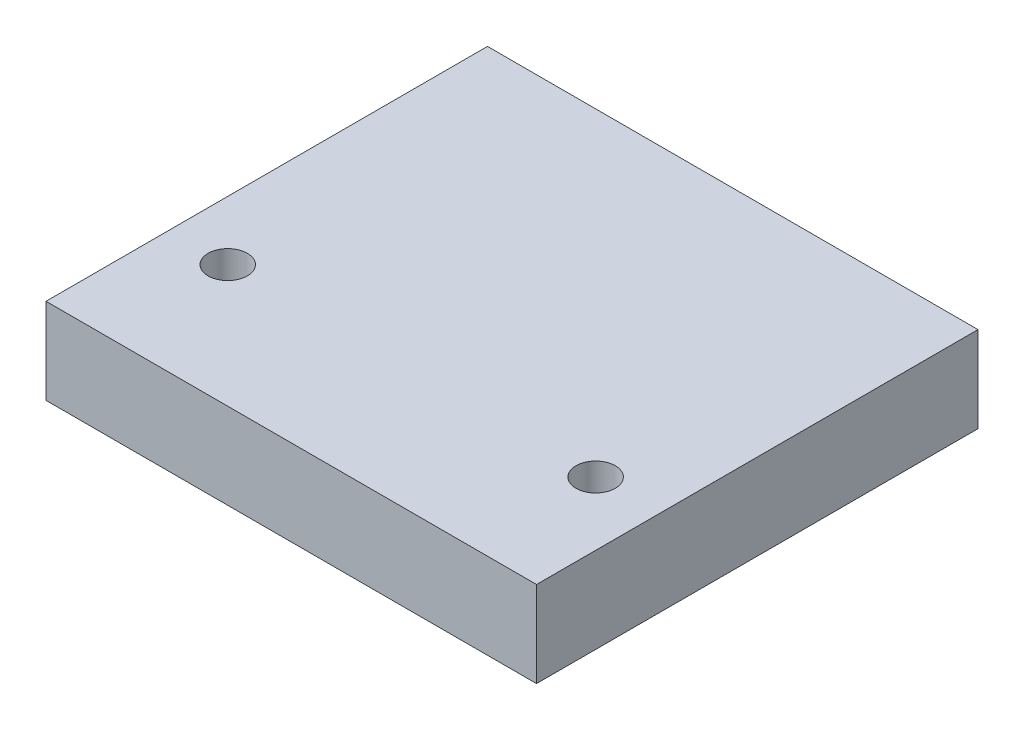
SolidWorks part; units mm, degrees
ref_plane "前视基准面" through (0, 0, 0) normal (0, 0, 1) x (1, 0, 0)
ref_plane "上视基准面" through (0, 0, 0) normal (0, 1, 0) x (1, 0, 0)
ref_plane "右视基准面" through (0, 0, 0) normal (1, 0, 0) x (0, 0, -1)
other "Configuration Table"
sketch "草图1" plane through (0, 0, 0) normal (0, 0, 1) x (1, 0, 0)
  line L1 (-6.9655, 0.3299) -> (13.0345, 0.3299)
  line L2 (-6.9655, 0.3299) -> (-6.9655, -3.1701)
  line L3 (-6.9655, -3.1701) -> (13.0345, -3.1701)
  line L4 (13.0345, 0.3299) -> (13.0345, -3.1701)
  dimension "D1" = 20
  dimension "D2" = 3.5
extrude "凸台-拉伸1" add sketch "草图1" along normal blind 18
sketch "草图2" plane through (0, 0.3299, 0) normal (0, 1, 0) x (1, 0, 0)
  line L0 (-9.123, -13) -> (16.0233, -13) construction
  line L1 (-6.9655, -18) -> (-6.9655, 0) construction
  line L2 (13.0345, -18) -> (-6.9655, -18) construction
  circle A0 centre (-4.5555, -13) radius 0.8
  circle A1 centre (10.4445, -13) radius 0.8
  dimension "D1" = 2.41
  dimension "D2" = 15
  dimension "D3" = 5
extrude "切除-拉伸1" cut sketch "草图2" against normal through all
sketch "草图3" plane through (-6.9655, 0, 0) normal (-1, 0, 0) x (0, 0, 1)
  line L0 (0, -1.4201) -> (18, -1.4201) construction
  line L1 (0, 0.3299) -> (0, -3.1701) construction
  line L2 (18, 0.3299) -> (18, -3.1701) construction
  circle A0 centre (2, -1.4201) radius 0.8
  circle A1 centre (8, -1.4201) radius 0.8
  point P4 (8, -1.4201)
  point P7 (2, -1.4201)
  dimension "D1" = 2
  dimension "D2" = 6
hole_wizard "M1.6 螺纹孔1" positions "草图3" profile "草图5" tap size "M1.6" standard "GB"
cosmetic thread "孔螺蚊线1" parameters "D1"=2.4, "D2"=1.6
cosmetic thread "孔螺蚊线2" parameters "D1"=2.4, "D2"=1.6
sketch "草图5" plane through (-6.9655, -1.4201, 2) normal (0, 1, 0) x (0, 0, 1)
  line L0 (0, 0) -> (0, 4.3755)
  line L1 (0, 4.3755) -> (0.625, 4)
  line L2 (0.625, 4) -> (0.625, 0)
  line L5 (0.625, 0) -> (0, 0)
  line L10 (0, 4.3755) -> (-0.625, 4) construction
  line L11 (0, -6.35) -> (0, 107.95) construction
  dimension "螺纹孔钻头直径" = 1.25
  dimension "螺纹孔钻头深度" = 4
  dimension "导头角度" = 118
